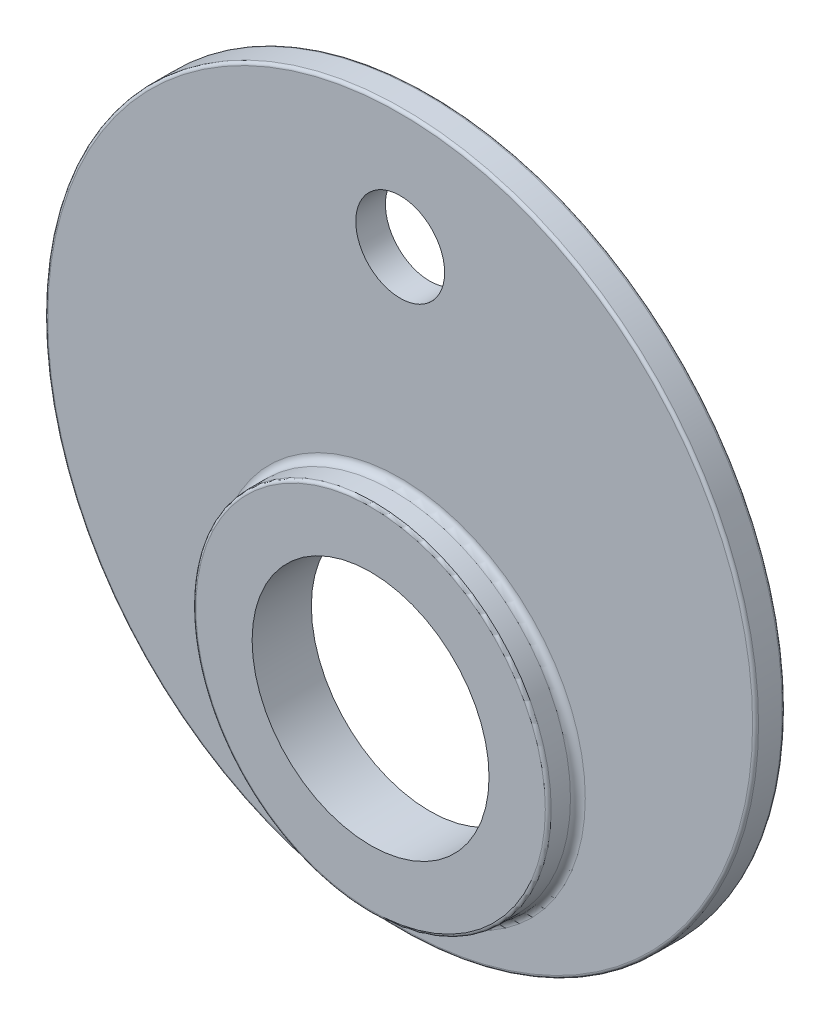
SolidWorks part; units mm, degrees
ref_plane "Front Plane" through (0, 0, 0) normal (0, 0, 1) x (1, 0, 0)
ref_plane "Top Plane" through (0, 0, 0) normal (0, 1, 0) x (1, 0, 0)
ref_plane "Right Plane" through (0, 0, 0) normal (1, 0, 0) x (0, 0, -1)
sketch "Sketch1" plane through (0, 0, 0) normal (0, 0, 1) x (1, 0, 0)
  line L0 (0, 0) -> (0, 203.2) construction
  line L1 (0, 0) -> (0, -127) construction
  circle A0 centre (0, 0) radius 304.8
  circle A1 centre (0, -127) radius 101.6
  circle A2 centre (0, 203.2) radius 38.1
  dimension "D1" = 609.6
  dimension "D4" = 203.2
  dimension "D5" = 76.2
  dimension "D2" = 203.2
  dimension "D3" = 127
extrude "Boss-Extrude1" add sketch "Sketch1" along normal blind 25.4
sketch "Sketch2" plane through (0, 0, 25.4) normal (0, 0, 1) x (1, 0, 0)
  circle A0 centre (0, -127) radius 101.6
  circle A1 centre (0, -127) radius 152.4
  dimension "D1" = 304.8
extrude "Boss-Extrude2" add sketch "Sketch2" along normal blind 25.4
fillet "Fillet1" radius 2.54 3 edges at (304.8, 0, 25.4) (152.4, -127, 50.8) (304.8, 0, 0)
fillet "Fillet2" radius 6.35 1 edges at (152.4, -127, 25.4)
